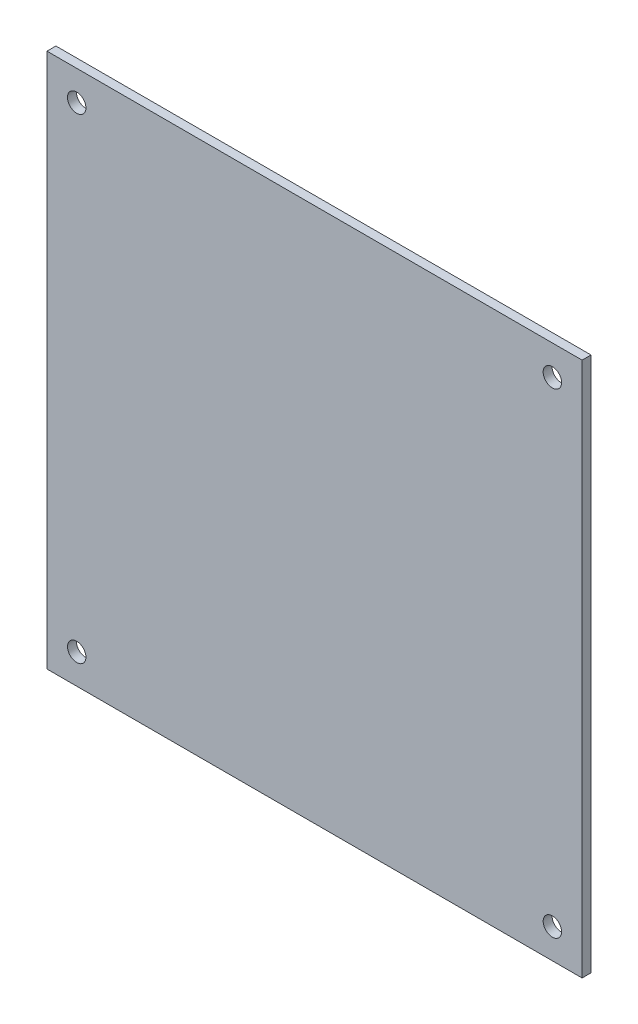
SolidWorks part; units mm, degrees
material "FR4"
ref_plane "Front Plane" through (0, 0, 0) normal (0, 0, 1) x (1, 0, 0)
ref_plane "Top Plane" through (0, 0, 0) normal (0, 1, 0) x (1, 0, 0)
ref_plane "Right Plane" through (0, 0, 0) normal (1, 0, 0) x (0, 0, -1)
sketch "Sketch1" plane through (0, 0, 0) normal (0, 0, 1) x (1, 0, 0)
  line L1 (45, -45) -> (-45, -45)
  line L2 (45, -45) -> (45, 45)
  line L3 (45, 45) -> (-45, 45)
  line L4 (-45, -45) -> (-45, 45)
  line L5 (45, -45) -> (-45, 45) construction
  line L6 (45, 45) -> (-45, -45) construction
  point P0 (0, 0)
  dimension "D1" = 90
  dimension "D2" = 90
extrude "Boss-Extrude1" add sketch "Sketch1" along normal blind 1.5
hole_wizard "Ø3.1 (3.1) Diameter Hole1" positions "Sketch3" profile "Sketch2" hole size "Ø3.1" standard "ANSI Metric" end condition through all
sketch "Sketch3" plane through (0, 0, 1.5) normal (0, 0, 1) x (1, 0, 0)
  line L2 (0, 0) -> (0, 57.4026) construction
  line L4 (0, 0) -> (61.2828, 0) construction
  point P0 (-40, 40)
  point P2 (40, 40)
  point P4 (40, -40)
  point P6 (-40, -40)
  point P36 (0.6631, -8.5562)
  dimension "D1" = 80
  dimension "D2" = 80
  dimension "D3" = 40
  dimension "D4" = 80
  dimension "D5" = 80
  dimension "D6" = 40
  dimension "D7" = 40
  dimension "D8" = 40
sketch "Sketch2" plane through (-40, 40, 1.5) normal (1, 0, 0) x (0, -1, 0)
  line L0 (0, 0) -> (0, 1.5)
  line L1 (0, 1.5) -> (1.55, 1.5)
  line L2 (1.55, 1.5) -> (1.55, 0)
  line L5 (1.55, 0) -> (0, 0)
  line L11 (0, -6.35) -> (0, 107.95) construction
  dimension "Thru Hole Dia." = 3.1
  dimension "Thru Hole Depth" = 1.5
